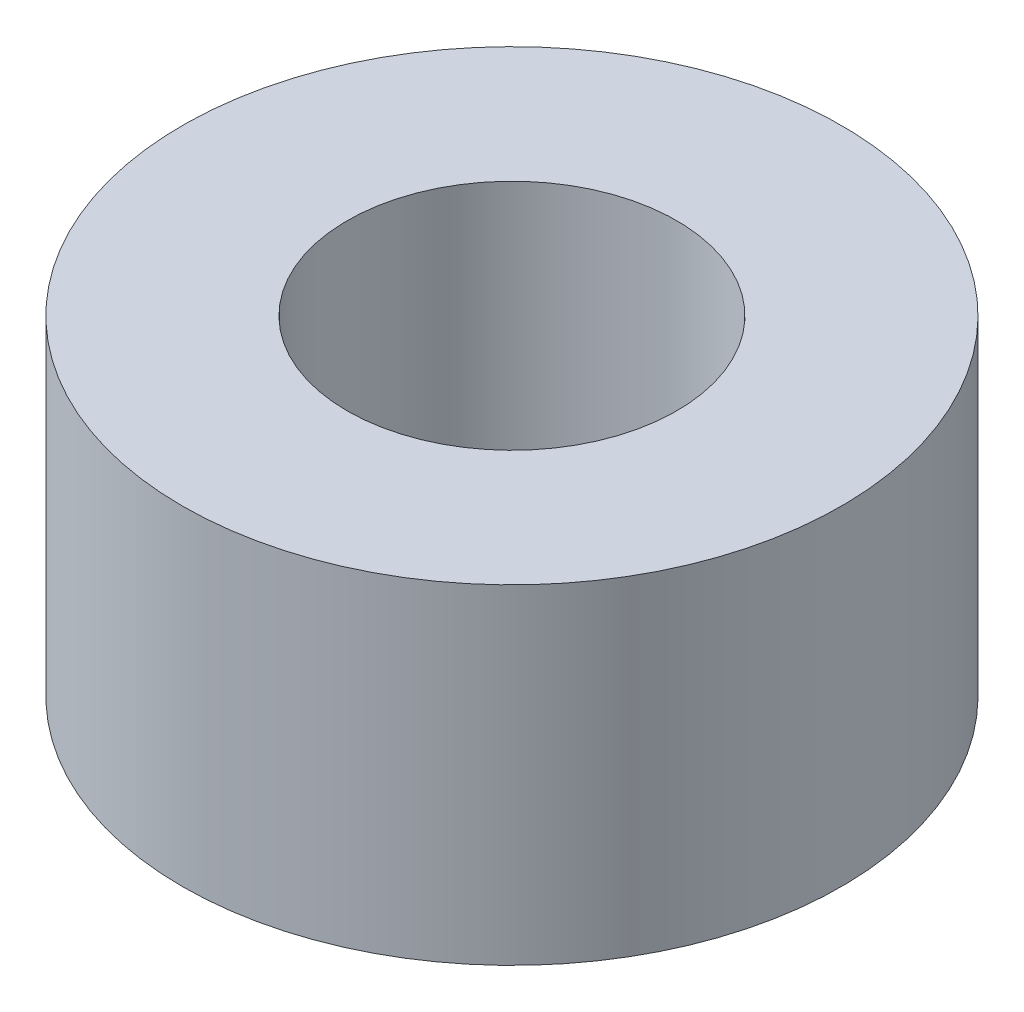
SolidWorks part; units mm, degrees
material "普通碳钢"
ref_plane "前视" through (0, 0, 0) normal (0, 0, 1) x (1, 0, 0)
ref_plane "上视" through (0, 0, 0) normal (0, 1, 0) x (1, 0, 0)
ref_plane "右视" through (0, 0, 0) normal (1, 0, 0) x (0, 0, -1)
sketch "草图1" plane through (0, 0, 0) normal (0, 1, 0) x (1, 0, 0)
  circle A0 centre (0, 0) radius 4
  circle A1 centre (0, 0) radius 2
  dimension "D1" = 8
  dimension "D2" = 4
extrude "凸台-拉伸1" add sketch "草图1" along normal blind 4
